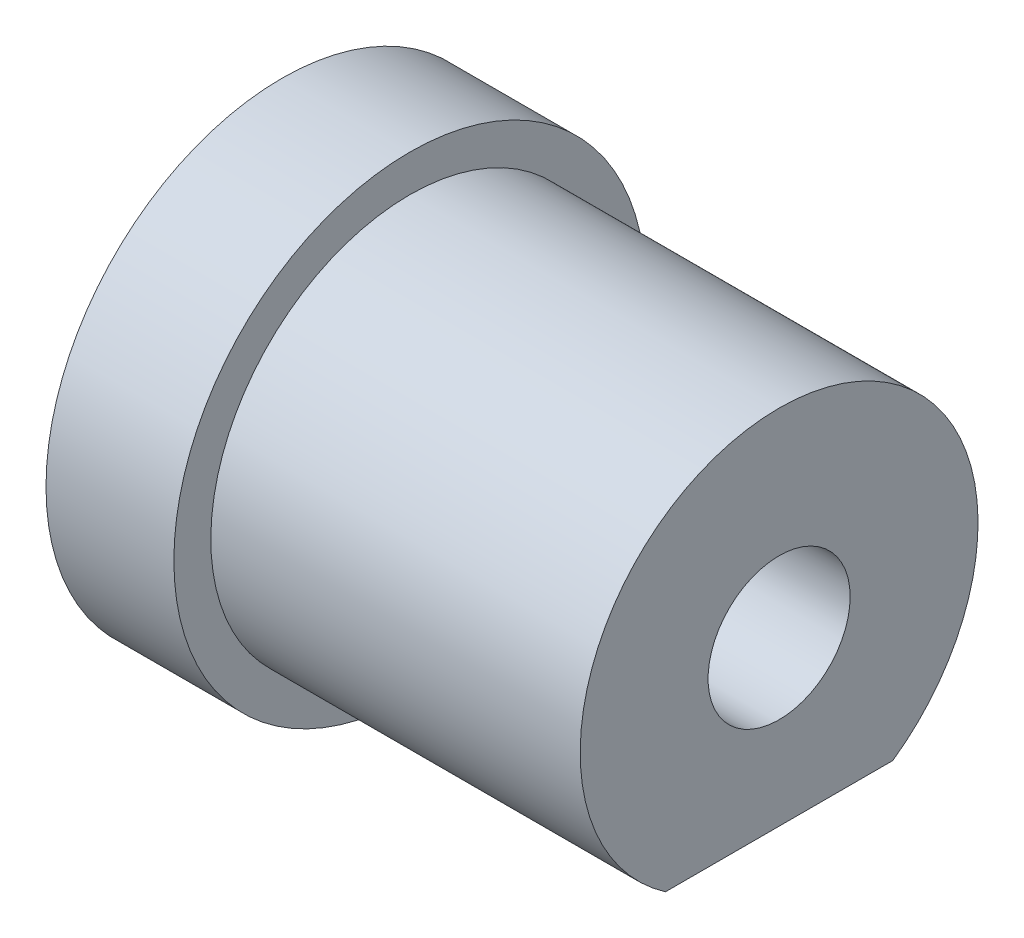
SolidWorks part; units mm, degrees
material "Полиэфирэфиркетон (ПЭЭК)"
ref_plane "Спереди" through (0, 0, 0) normal (0, 0, 1) x (1, 0, 0)
ref_plane "Сверху" through (0, 0, 0) normal (0, 1, 0) x (1, 0, 0)
ref_plane "Справа" through (0, 0, 0) normal (1, 0, 0) x (0, 0, -1)
sketch "Эскиз1" plane through (0, 0, 0) normal (1, 0, 0) x (0, 0, -1)
  circle A0 centre (0, 0) radius 8.3
  circle A1 centre (0, 0) radius 3.15
  dimension "D1" = 6.3
  dimension "D2" = 16.6
extrude "Бобышка-Вытянуть1" add sketch "Эскиз1" along normal blind 4.5 contours A0
sketch "Эскиз2" plane through (0, 0, 0) normal (-1, 0, 0) x (0, 0, 1)
  circle A0 centre (-0.2162, 0) radius 6.1
  dimension "D1" = 12.2
extrude "Вырез-Вытянуть1" cut sketch "Эскиз2" against normal blind 1.4
sketch "Эскиз3" plane through (4.5, 0, 0) normal (1, 0, 0) x (0, 0, -1)
  circle A0 centre (0, 0) radius 7
  dimension "D1" = 14
extrude "Бобышка-Вытянуть4" add sketch "Эскиз3" along normal blind 13
sketch "Эскиз9" plane through (17.5, 0, 0) normal (1, 0, 0) x (0, 0, -1)
  circle A0 centre (0, 0) radius 2.5
  dimension "D1" = 5
extrude "Вырез-Вытянуть7" cut sketch "Эскиз9" against normal through all
sketch "Эскиз10" plane through (17.5, 0, 0) normal (1, 0, 0) x (0, 0, -1)
  line L0 (-4, -5.7446) -> (4, -5.7446)
  circle A0 centre (0, 0) radius 7 construction
  arc A1 (-4, -5.7446) -> (4, -5.7446) centre (0, 0) ccw
  dimension "D1" = 8
extrude "Вырез-Вытянуть8" cut sketch "Эскиз10" against normal up to surface (13 mm away) contours L0 A1 up to face at (4.5, 0, -8.3)
sketch "Эскиз12" plane through (0, 0, 0) normal (-1, 0, 0) x (0, 0, 1)
  circle A0 centre (0, 0) radius 3.15
  dimension "D1" = 6.3
extrude "Вырез-Вытянуть9" cut sketch "Эскиз12" against normal blind 7
